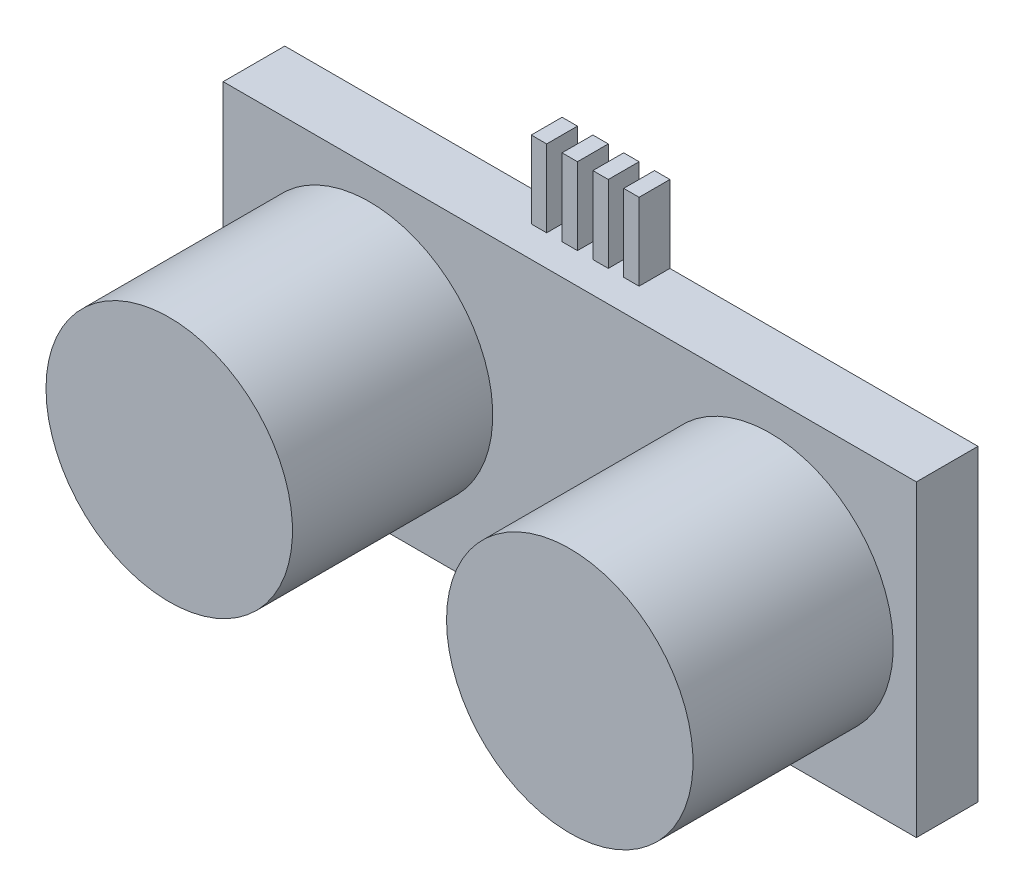
SolidWorks part; units mm, degrees
ref_plane "Front Plane" through (0, 0, 0) normal (0, 0, 1) x (1, 0, 0)
ref_plane "Top Plane" through (0, 0, 0) normal (0, 1, 0) x (1, 0, 0)
ref_plane "Right Plane" through (0, 0, 0) normal (1, 0, 0) x (0, 0, -1)
sketch "Sketch1" plane through (0, 0, 0) normal (0, 0, 1) x (1, 0, 0)
  line L1 (-22.5, -10) -> (22.5, -10)
  line L2 (-22.5, -10) -> (-22.5, 10)
  line L3 (-22.5, 10) -> (22.5, 10)
  line L4 (22.5, -10) -> (22.5, 10)
  line L5 (-22.5, -10) -> (22.5, 10) construction
  line L6 (-22.5, 10) -> (22.5, -10) construction
  point P0 (0, 0)
  dimension "D1" = 45
  dimension "D2" = 20
extrude "Boss-Extrude1" add sketch "Sketch1" along normal blind 4
sketch "Sketch2" plane through (0, 0, 4) normal (0, 0, 1) x (1, 0, 0)
  circle A3 centre (-13, 0) radius 8
  circle A4 centre (13, 0) radius 8
extrude "Boss-Extrude2" add sketch "Sketch2" along normal blind 13
sketch "Sketch4" plane through (0, 0, 0) normal (0, 0, -1) x (-1, 0, 0)
  line L0 (2, 15) -> (1.5, 15)
  line L1 (-22.5, 10) -> (22.5, 10) construction
  line L2 (0, 15) -> (-0.5, 15)
  line L3 (-0.5, 15) -> (-0.5, 10)
  line L4 (-0.5, 10) -> (0.5, 10)
  line L5 (0.5, 10) -> (0.5, 15)
  line L6 (0.5, 15) -> (0, 15)
  line L7 (1.5, 15) -> (1.5, 10)
  line L8 (2.5, 10) -> (2.5, 15)
  line L9 (2.5, 15) -> (2, 15)
  line L10 (4, 15) -> (3.5, 15)
  line L11 (3.5, 15) -> (3.5, 10)
  line L12 (4.5, 10) -> (4.5, 15)
  line L13 (4.5, 15) -> (4, 15)
  line L14 (-2, 15) -> (-2.5, 15)
  line L15 (-2.5, 15) -> (-2.5, 10)
  line L16 (-2.5, 10) -> (-1.5, 10)
  line L17 (-1.5, 10) -> (-1.5, 15)
  line L18 (-1.5, 15) -> (-2, 15)
  line L19 (3.5, 10) -> (4.5, 10)
  line L20 (1.5, 10) -> (2.5, 10)
  dimension "D1" = 3
  dimension "D2" = 2
extrude "Boss-Extrude3" add sketch "Sketch4" against normal blind 2
